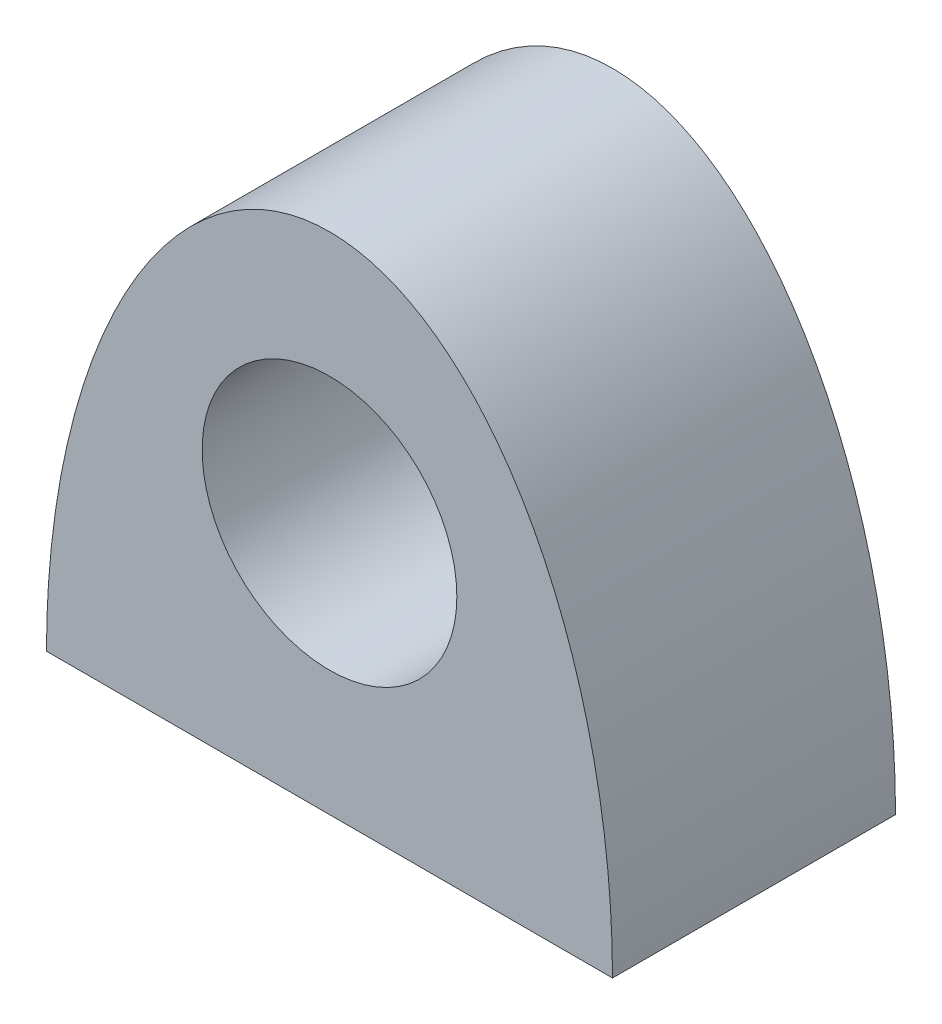
SolidWorks part; units mm, degrees
ref_plane "Front Plane" through (0, 0, 0) normal (0, 0, 1) x (1, 0, 0)
ref_plane "Top Plane" through (0, 0, 0) normal (0, 1, 0) x (1, 0, 0)
ref_plane "Right Plane" through (0, 0, 0) normal (1, 0, 0) x (0, 0, -1)
sketch "Sketch1" plane through (0, 0, 0) normal (0, 0, 1) x (1, 0, 0)
  line L0 (0, 0) -> (6, 0)
  line L1 (3, 0) -> (3, 5.3514) construction
  circle A0 centre (3, 2.6757) radius 1.35
  ellipse E0 centre (3, 0) end of major axis (3, -5.3514) minor radius 3 (6, 0) -> (0, 0) ccw
  point P10 (3, 2.6757)
  dimension "D2" = 2.7
  dimension "D1" = 6
extrude "Boss-Extrude1" add sketch "Sketch1" along normal blind 3
